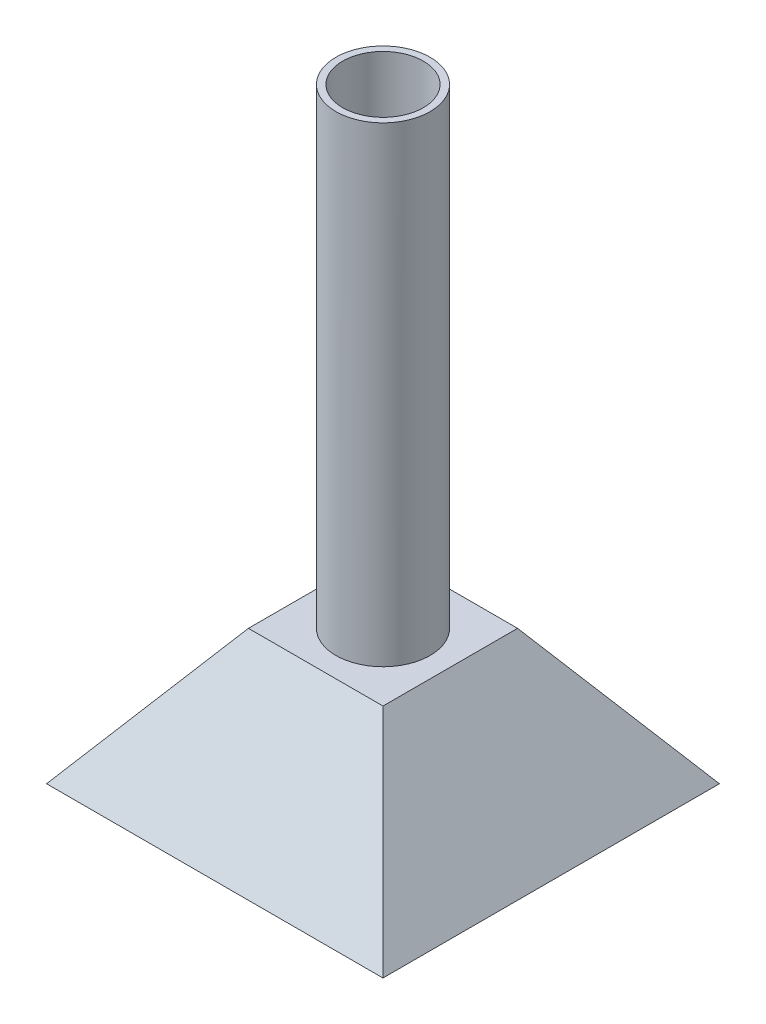
SolidWorks part; units mm, degrees
ref_plane "Front Plane" through (0, 0, 0) normal (0, 0, 1) x (1, 0, 0)
ref_plane "Top Plane" through (0, 0, 0) normal (0, 1, 0) x (1, 0, 0)
ref_plane "Right Plane" through (0, 0, 0) normal (1, 0, 0) x (0, 0, -1)
sketch "Sketch1" plane through (0, 0, 0) normal (0, 1, 0) x (1, 0, 0)
  line L1 (-63.5, -63.5) -> (63.5, -63.5)
  line L2 (-63.5, -63.5) -> (-63.5, 63.5)
  line L3 (-63.5, 63.5) -> (63.5, 63.5)
  line L4 (63.5, -63.5) -> (63.5, 63.5)
  line L5 (-63.5, -63.5) -> (63.5, 63.5) construction
  line L6 (-63.5, 63.5) -> (63.5, -63.5) construction
  point P0 (0, 0)
  dimension "D1" = 127
ref_plane "Plane1" through (0, 50.8, 0) normal (0, 1, 0) x (1, 0, 0)
sketch "Sketch2" plane through (0, 50.8, 0) normal (0, 1, 0) x (1, 0, 0)
  line L1 (-25.4, -25.4) -> (25.4, -25.4)
  line L2 (-25.4, -25.4) -> (-25.4, 25.4)
  line L3 (-25.4, 25.4) -> (25.4, 25.4)
  line L4 (25.4, -25.4) -> (25.4, 25.4)
  line L5 (-25.4, -25.4) -> (25.4, 25.4) construction
  line L6 (-25.4, 25.4) -> (25.4, -25.4) construction
  point P0 (0, 0)
  dimension "D1" = 50.8
loft "Loft1" add profiles "Sketch2", "Sketch1"
sketch "Sketch3" plane through (0, 50.8, 0) normal (0, 1, 0) x (1, 0, 0)
  circle A0 centre (0, 0) radius 15.24
  circle A1 centre (0, 0) radius 17.78
  dimension "D1" = 30.48
  dimension "D2" = 2.54
extrude "Boss-Extrude1" add sketch "Sketch3" along normal blind 177.8
